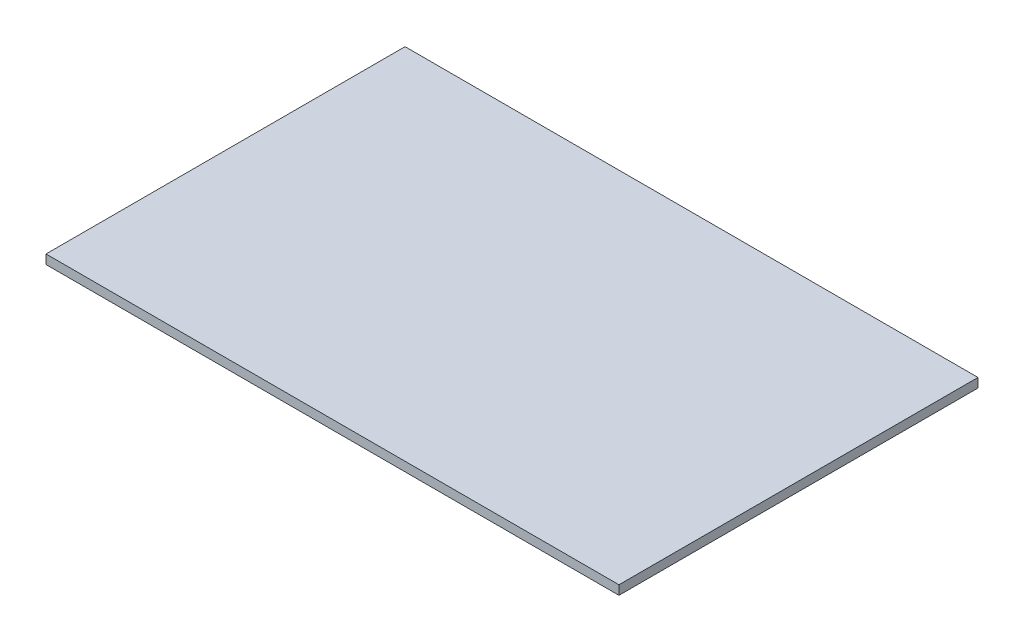
SolidWorks part; units mm, degrees
ref_plane "Front Plane" through (0, 0, 0) normal (0, 0, 1) x (1, 0, 0)
ref_plane "Top Plane" through (0, 0, 0) normal (0, 1, 0) x (1, 0, 0)
ref_plane "Right Plane" through (0, 0, 0) normal (1, 0, 0) x (0, 0, -1)
sketch "Sketch1" plane through (0, 0, 0) normal (0, 1, 0) x (1, 0, 0)
  line L1 (-375, -235) -> (375, -235)
  line L2 (-375, -235) -> (-375, 235)
  line L3 (-375, 235) -> (375, 235)
  line L4 (375, -235) -> (375, 235)
  line L5 (-375, -235) -> (375, 235) construction
  line L6 (-375, 235) -> (375, -235) construction
  point P0 (0, 0)
  dimension "D1" = 750
  dimension "D2" = 470
extrude "Boss-Extrude1" add sketch "Sketch1" along normal blind 12
equation "\"Case_Width\" = 750mm"
equation "\"Case_Depth\" = 470mm"
equation "\"D1@Sketch1\"=\"Case_Width\""
equation "\"D2@Sketch1\"=\"Case_Depth\""
equation "\"Tank_Width\" = 710mm"
equation "\"WoodSheet_Thickness\" = 12mm"
equation "\"D1@Boss-Extrude1\"=\"WoodSheet_Thickness\""
